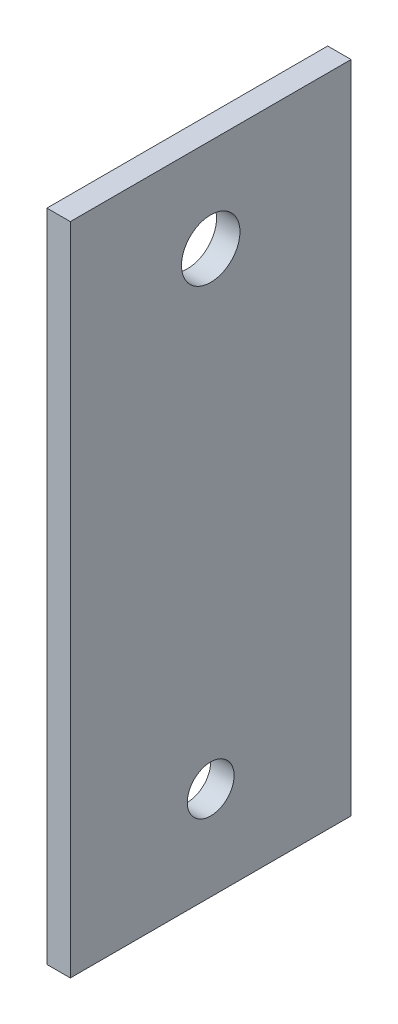
SolidWorks part; units mm, degrees
ref_plane "Front Plane" through (0, 0, 0) normal (0, 0, 1) x (1, 0, 0)
ref_plane "Top Plane" through (0, 0, 0) normal (0, 1, 0) x (1, 0, 0)
ref_plane "Right Plane" through (0, 0, 0) normal (1, 0, 0) x (0, 0, -1)
sketch "Sketch1" plane through (0, 0, 0) normal (1, 0, 0) x (0, 0, -1)
  line L0 (0, -31.75) -> (0, 31.75) construction
  line L1 (-19.05, -44.45) -> (19.05, -44.45)
  line L2 (-19.05, -44.45) -> (-19.05, 44.45)
  line L3 (-19.05, 44.45) -> (19.05, 44.45)
  line L4 (19.05, -44.45) -> (19.05, 44.45)
  line L5 (-19.05, -44.45) -> (19.05, 44.45) construction
  line L6 (-19.05, 44.45) -> (19.05, -44.45) construction
  circle A0 centre (0, 31.75) radius 3.9688
  circle A1 centre (0, -31.75) radius 3.175
  point P0 (0, 0)
  point P9 (0, 0)
  dimension "D4" = 7.9375
  dimension "D5" = 6.35
  dimension "D1" = 38.1
  dimension "D2" = 88.9
  dimension "D3" = 63.5
extrude "Boss-Extrude1" add sketch "Sketch1" along normal blind 3.175
